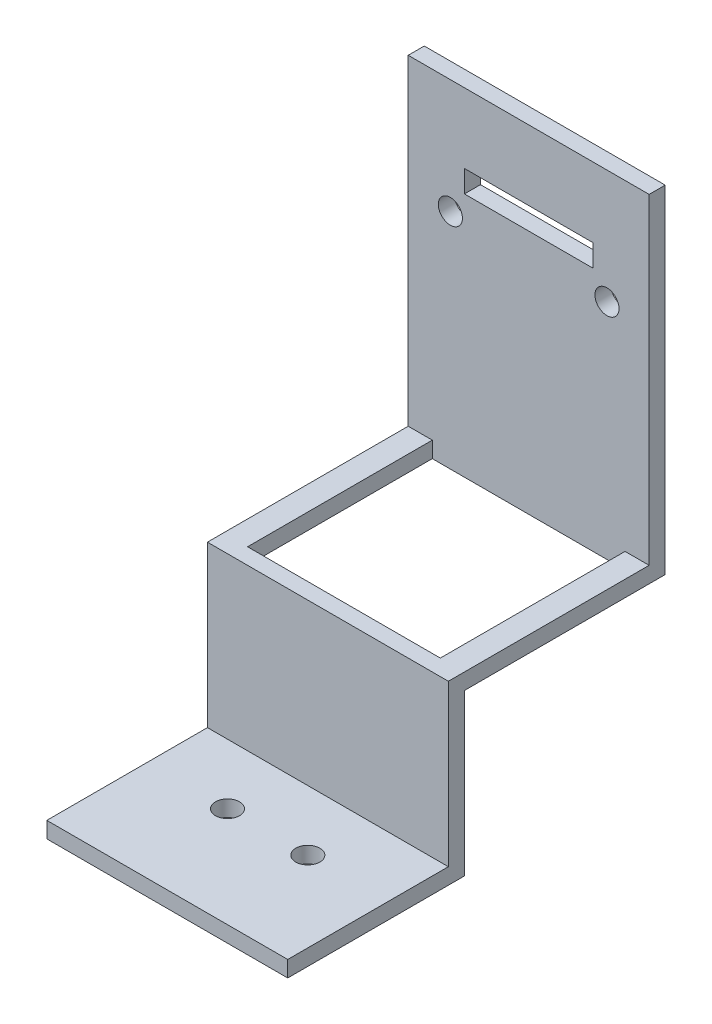
SolidWorks part; units mm, degrees
ref_plane "Front Plane" through (0, 0, 0) normal (0, 0, 1) x (1, 0, 0)
ref_plane "Top Plane" through (0, 0, 0) normal (0, 1, 0) x (1, 0, 0)
ref_plane "Right Plane" through (0, 0, 0) normal (1, 0, 0) x (0, 0, -1)
sketch "Sketch1" plane through (0, 0, 0) normal (0, 0, 1) x (1, 0, 0)
  line L1 (0, 0) -> (30, 0)
  line L2 (0, 0) -> (0, 40)
  line L3 (0, 40) -> (30, 40)
  line L4 (30, 0) -> (30, 40)
  dimension "D1" = 30
  dimension "D2" = 40
extrude "Boss-Extrude1" add sketch "Sketch1" along normal blind 2
sketch "Sketch5" plane through (0, 0, 0) normal (1, 0, 0) x (0, 0, -1)
  line L1 (-27, -20) -> (-47, -20)
  line L2 (-47, -20) -> (-47, -22)
  line L3 (-47, -22) -> (-26.3, -22)
  line L5 (0, 0) -> (-2, 0)
  line L6 (-27, -20) -> (-27, 0)
  line L7 (-27, 0) -> (-2, 0)
  line L8 (0, 0) -> (0, -2)
  line L9 (0, -2) -> (-25, -2)
  line L10 (-25, -2) -> (-25, -22)
  line L11 (-25, -22) -> (-26.3, -22)
  dimension "D1" = 2
  dimension "D2" = 20
  dimension "D3" = 20.7
  dimension "D4" = 20
  dimension "D5" = 2
  dimension "D6" = 2
  dimension "D7" = 25
extrude "Boss-Extrude3" add sketch "Sketch5" along normal blind 30
sketch "Sketch6" plane through (0, 0, 0) normal (0, 1, 0) x (1, 0, 0)
  line L0 (0, -2) -> (30, -2) construction
  line L1 (27, -2) -> (3, -2)
  line L2 (27, -2) -> (27, -25)
  line L3 (27, -25) -> (3, -25)
  line L4 (3, -2) -> (3, -25)
  line L5 (30, -27) -> (0, -27) construction
  line L6 (30, -2) -> (30, -27) construction
  line L7 (0, -2) -> (0, -27) construction
  dimension "D1" = 2
  dimension "D2" = 3
  dimension "D3" = 3
extrude "Cut-Extrude2" cut sketch "Sketch6" against normal blind 2
sketch "Sketch7" plane through (0, 0, 0) normal (0, 0, -1) x (-1, 0, 0)
  line L0 (-30, -2) -> (-30, 40) construction
  line L1 (-23, 31.2976) -> (-7, 31.2976)
  line L2 (-23, 31.2976) -> (-23, 28.5476)
  line L3 (-23, 28.5476) -> (-7, 28.5476)
  line L4 (-7, 31.2976) -> (-7, 28.5476)
  circle A0 centre (-24.75, 25.7976) radius 1.5
  circle A1 centre (-5.25, 25.7976) radius 1.5
  dimension "D4" = 1.75
  dimension "D1" = 2.75
  dimension "D2" = 16
  dimension "D3" = 7
  dimension "D5" = 1.75
  dimension "D6" = 5.5
  dimension "D7" = 5.5
extrude "Cut-Extrude3" cut sketch "Sketch7" against normal blind 10
sketch "Sketch9" plane through (0, -22, 0) normal (0, -1, 0) x (1, 0, 0)
  line L0 (30, 47) -> (30, 25) construction
  line L1 (30, 25) -> (0, 25) construction
  circle A0 centre (20, 34.5) radius 1.5
  circle A1 centre (10, 34.5) radius 1.5
  dimension "D1" = 10
  dimension "D2" = 10
  dimension "D3" = 9.5
  dimension "D4" = 9.5
extrude "Cut-Extrude4" cut sketch "Sketch9" against normal blind 10
